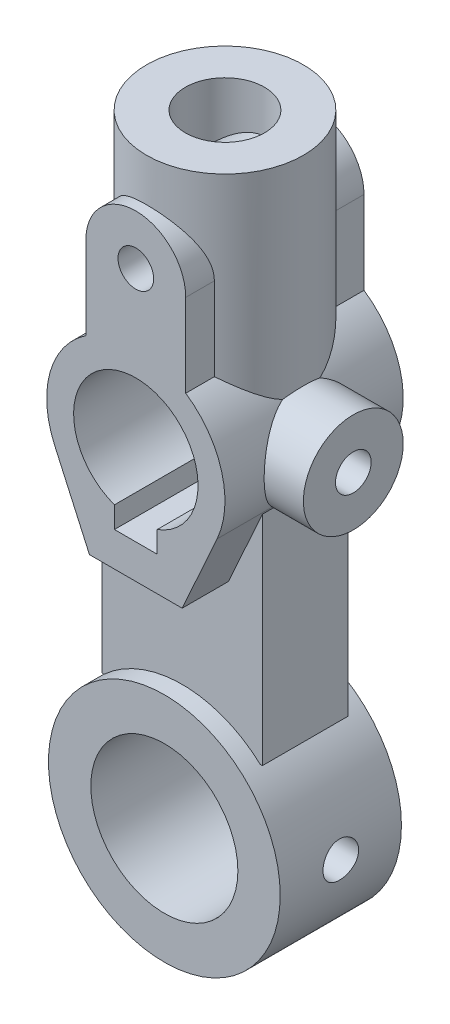
SolidWorks part; units mm, degrees
ref_plane "Front Plane" through (0, 0, 0) normal (0, 0, 1) x (1, 0, 0)
ref_plane "Top Plane" through (0, 0, 0) normal (0, 1, 0) x (1, 0, 0)
ref_plane "Right Plane" through (0, 0, 0) normal (1, 0, 0) x (0, 0, -1)
sketch "Sketch1" plane through (0, 0, 0) normal (0, 0, 1) x (1, 0, 0)
  circle A0 centre (0, 0) radius 20.625
  circle A1 centre (0, 0) radius 32.5
  dimension "D1" = 41.25
  dimension "D2" = 65
extrude "Boss-Extrude1" add sketch "Sketch1" against normal mid plane 34
sketch "Sketch2" plane through (0, 0, 0) normal (0, 1, 0) x (1, 0, 0)
  line L0 (0, 0) -> (0, 17) construction
  line L1 (-22.5, -12) -> (22.5, -12)
  line L2 (-22.5, -12) -> (-22.5, 12)
  line L3 (-22.5, 12) -> (22.5, 12)
  line L4 (22.5, -12) -> (22.5, 12)
  line L5 (-22.5, -12) -> (22.5, 12) construction
  line L6 (-22.5, 12) -> (22.5, -12) construction
  line L7 (32.5, 17) -> (-32.5, 17) construction
  point P0 (0, 0)
  dimension "D1" = 24
  dimension "D2" = 45
extrude "Boss-Extrude2" add sketch "Sketch2" along normal blind 72 from offset 24 contours L3 L4 L1 L2
sketch "Sketch4" plane through (0, 0, 0) normal (1, 0, 0) x (0, 0, -1)
  circle A0 centre (0, 0) radius 5
  dimension "D1" = 10
extrude "Cut-Extrude1" cut sketch "Sketch4" along normal through all
sketch "Sketch7" plane through (0, 0, 0) normal (0, 0, 1) x (1, 0, 0)
  line L0 (0, 96) -> (0, 0) construction
  line L1 (-13, 64) -> (13, 64)
  line L4 (-6, 73.61) -> (6, 73.61)
  line L5 (-6, 73.61) -> (-6, 79.614)
  line L6 (6, 73.61) -> (6, 79.614)
  line L7 (0, 96) -> (0, 140) construction
  line L8 (-14, 140) -> (-14, 116.7123)
  line L9 (14, 140) -> (14, 116.7123)
  line L10 (-13, 64) -> (-22.7923, 85.7281)
  line L11 (13, 64) -> (22.7923, 85.7281)
  arc A0 (6, 79.614) -> (-6, 79.614) centre (0, 96) ccw
  arc A1 (22.7923, 85.7281) -> (14, 116.7123) centre (0, 96) ccw
  arc A2 (14, 140) -> (-14, 140) centre (0, 140) ccw
  circle A3 centre (0, 140) radius 5
  arc A4 (-14, 116.7123) -> (-22.7923, 85.7281) centre (0, 96) ccw
  dimension "D2" = 34.9
  dimension "D3" = 50
  dimension "D8" = 44
  dimension "D9" = 28
  dimension "D10" = 10
  dimension "D1" = 96
  dimension "D4" = 26
  dimension "D5" = 32
  dimension "D6" = 12
  dimension "D7" = 22.39
extrude "Boss-Extrude3" add sketch "Sketch7" along normal mid plane 50
ref_plane "Plane1" through (0, 166, 0) normal (0, 1, 0) x (1, 0, 0)
sketch "Sketch8" plane through (0, 166, 0) normal (0, 1, 0) x (1, 0, 0)
  circle A0 centre (0, 0) radius 22
  circle A1 centre (0, 0) radius 11.1
  dimension "D1" = 22.2
  dimension "D2" = 44
extrude "Boss-Extrude4" add sketch "Sketch8" against normal up to next
ref_plane "Plane2" through (36, 0, 0) normal (1, 0, 0) x (0, 0, -1)
sketch "Sketch10" plane through (36, 0, 0) normal (1, 0, 0) x (0, 0, -1)
  line L0 (0, 0) -> (0, 96) construction
  circle A0 centre (0, 96) radius 5
  circle A1 centre (0, 96) radius 14
  dimension "D2" = 28
  dimension "D3" = 10
  dimension "D1" = 96
extrude "Boss-Extrude5" add sketch "Sketch10" against normal up to next
sketch "Sketch14" plane through (36, 0, 0) normal (1, 0, 0) x (0, 0, -1)
  circle A0 centre (0, 96) radius 5 construction
  circle A1 centre (0, 96) radius 5
extrude "Cut-Extrude3" cut sketch "Sketch14" against normal blind 34
sketch "Sketch15" plane through (0, 0, 12) normal (0, 0, 1) x (1, 0, 0)
  line L4 (6, 73.61) -> (6, 79.614)
  line L5 (17.45, 96) -> (-17.45, 96)
  line L6 (-6, 79.614) -> (-6, 73.61)
  line L7 (-6, 73.61) -> (6, 73.61)
  line L8 (6, 73.61) -> (6, 79.614)
  line L9 (17.45, 96) -> (-17.45, 96)
  line L10 (-6, 79.614) -> (-6, 73.61)
  line L11 (-6, 73.61) -> (6, 73.61)
  arc A2 (6, 79.614) -> (17.45, 96) centre (0, 96) ccw
  arc A3 (-17.45, 96) -> (-6, 79.614) centre (0, 96) ccw
  arc A4 (6, 79.614) -> (17.45, 96) centre (0, 96) ccw
  arc A5 (-17.45, 96) -> (-6, 79.614) centre (0, 96) ccw
  dimension "D1" = 0
extrude "Cut-Extrude4" cut sketch "Sketch15" against normal up to next
